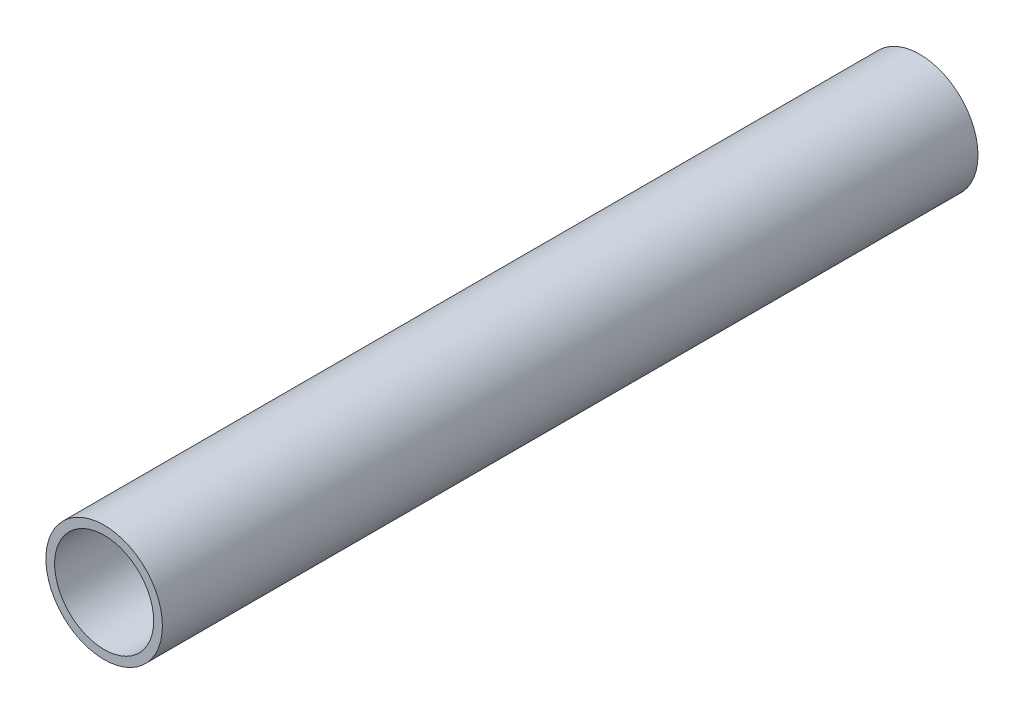
SolidWorks part; units mm, degrees
material "PE Высокой плотности"
ref_plane "Front" through (0, 0, 0) normal (0, 0, 1) x (1, 0, 0)
ref_plane "Top" through (0, 0, 0) normal (0, 1, 0) x (1, 0, 0)
ref_plane "Side" through (0, 0, 0) normal (1, 0, 0) x (0, 0, -1)
sketch "PipeSketch" plane through (0, 0, 0) normal (0, 0, 1) x (1, 0, 0)
  circle A0 centre (0, 0) radius 10
  circle A1 centre (0, 0) radius 8.5
  dimension "OuterDiameter" = 20
  dimension "InnerDiameter" = 17
extrude "Extrusion" add sketch "PipeSketch" along normal blind 140
sketch "FilterSketch" plane through (0, 0, 0) normal (0, 0, 1) x (1, 0, 0)
  circle A0 centre (0, 0) radius 10 construction
  dimension "NominalDiameter" = 20
